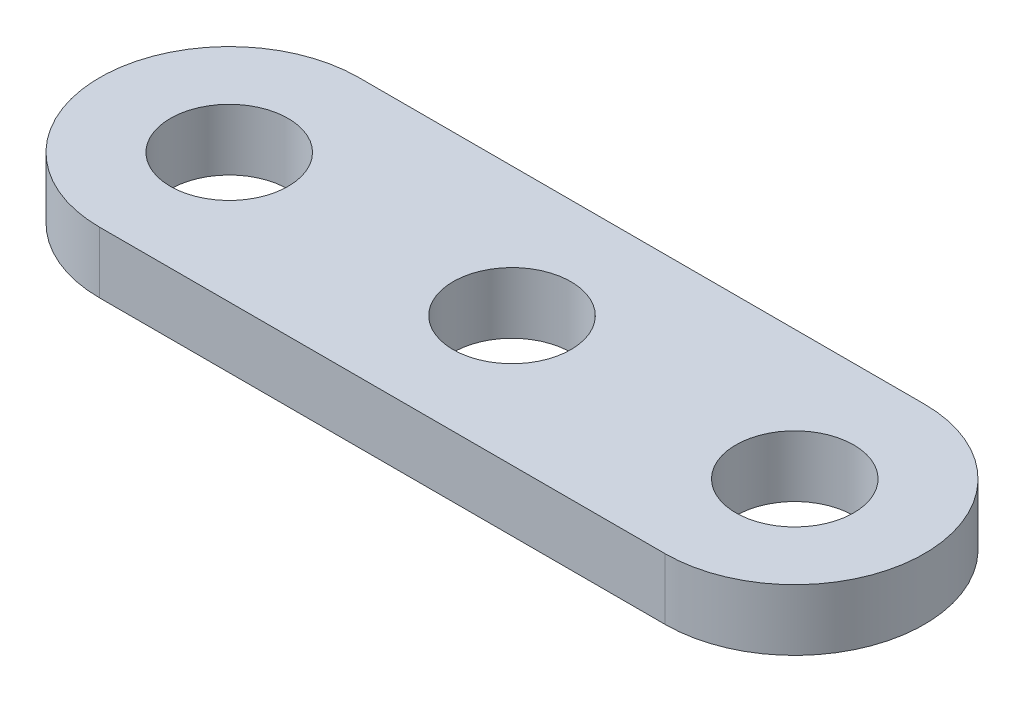
SolidWorks part; units mm, degrees
ref_plane "前视基准面" through (0, 0, 0) normal (0, 0, 1) x (1, 0, 0)
ref_plane "上视基准面" through (0, 0, 0) normal (0, 1, 0) x (1, 0, 0)
ref_plane "右视基准面" through (0, 0, 0) normal (1, 0, 0) x (0, 0, -1)
other "Configuration Table"
sketch "草图1" plane through (0, 0, 0) normal (0, 1, 0) x (1, 0, 0)
  line L0 (-12, 0) -> (12, 0) construction
  line L1 (-12, 5.5) -> (12, 5.5)
  line L2 (-12, -5.5) -> (12, -5.5)
  line L3 (0, 0) -> (0, 5.5) construction
  arc A0 (-12, 5.5) -> (-12, -5.5) centre (-12, 0) ccw
  arc A1 (12, -5.5) -> (12, 5.5) centre (12, 0) ccw
  circle A2 centre (-12, 0) radius 2.5
  circle A3 centre (0, 0) radius 2.5
  circle A4 centre (12, 0) radius 2.5
  point P2 (0, 0)
  dimension "D2" = 5.5
  dimension "D3" = 5
  dimension "D4" = 5
  dimension "D1" = 24
extrude "凸台-拉伸1" add sketch "草图1" along normal blind 2.6
